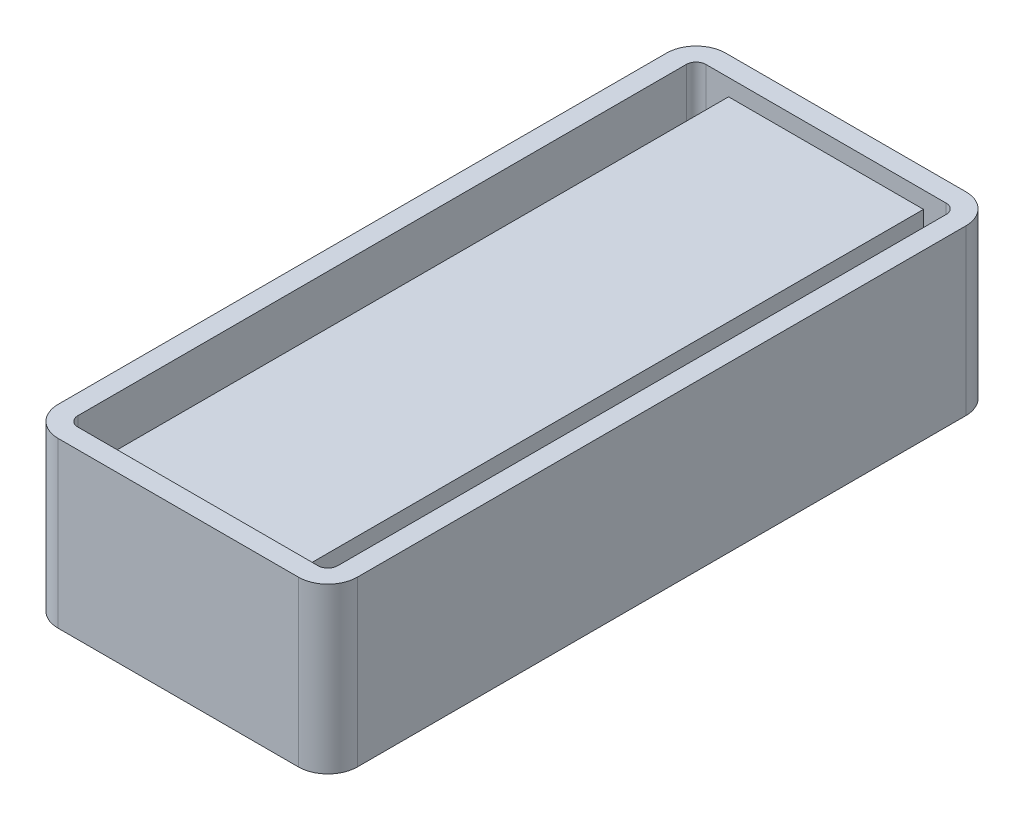
SolidWorks part; units mm, degrees
ref_plane "Front Plane" through (0, 0, 0) normal (0, 0, 1) x (1, 0, 0)
ref_plane "Top Plane" through (0, 0, 0) normal (0, 1, 0) x (1, 0, 0)
ref_plane "Right Plane" through (0, 0, 0) normal (1, 0, 0) x (0, 0, -1)
sketch "Sketch1" plane through (0, 0, 0) normal (0, 1, 0) x (1, 0, 0)
  line L0 (-15.2, 30.9) -> (-15.2, -30.9)
  line L1 (-9.9, 31.9) -> (9.9, 31.9)
  line L2 (-9.9, 31.9) -> (-9.9, -31.9)
  line L3 (-9.9, -31.9) -> (9.9, -31.9)
  line L4 (9.9, 31.9) -> (9.9, -31.9)
  line L5 (-9.9, 31.9) -> (9.9, -31.9) construction
  line L6 (-9.9, -31.9) -> (9.9, 31.9) construction
  line L7 (-12.2, 31.9) -> (12.2, 31.9)
  line L8 (-13.2, 30.9) -> (-13.2, -30.9)
  line L9 (-12.2, -31.9) -> (12.2, -31.9)
  line L10 (13.2, 30.9) -> (13.2, -30.9)
  line L11 (-13.2, 31.9) -> (13.2, -31.9) construction
  line L12 (-13.2, -31.9) -> (13.2, 31.9) construction
  line L13 (-12.2, -33.9) -> (12.2, -33.9)
  line L14 (15.2, 30.9) -> (15.2, -30.9)
  line L15 (-12.2, 33.9) -> (12.2, 33.9)
  arc A0 (-13.2, -30.9) -> (-12.2, -31.9) centre (-12.2, -30.9) ccw
  arc A1 (12.2, -31.9) -> (13.2, -30.9) centre (12.2, -30.9) ccw
  arc A2 (12.2, 31.9) -> (13.2, 30.9) centre (12.2, 30.9) cw
  arc A3 (-12.2, 31.9) -> (-13.2, 30.9) centre (-12.2, 30.9) ccw
  arc A4 (-15.2, -30.9) -> (-12.2, -33.9) centre (-12.2, -30.9) ccw
  arc A5 (12.2, -33.9) -> (15.2, -30.9) centre (12.2, -30.9) ccw
  arc A6 (12.2, 33.9) -> (15.2, 30.9) centre (12.2, 30.9) cw
  arc A7 (-12.2, 33.9) -> (-15.2, 30.9) centre (-12.2, 30.9) ccw
  point P0 (0, 0)
  point P6 (0, 0)
  point P11 (0, 0)
  dimension "D4" = 1
  dimension "D1" = 19.8
  dimension "D2" = 63.8
  dimension "D3" = 3.3
  dimension "D5" = 2
extrude "Boss-Extrude1" add sketch "Sketch1" along normal blind 15 contours L2 L9 L4 L7 | L15 A7 L0 A4 L13 A5 L14 A6 A3 L7 L2 L1 L4 A2 L10 A1 L9 L3 A0 L8
sketch "Sketch2" plane through (0, 15, 0) normal (0, 1, 0) x (1, 0, 0)
  line L0 (12.2, 31.9) -> (-12.2, 31.9)
  line L1 (-13.2, 30.9) -> (-13.2, -30.9)
  line L2 (-12.2, -31.9) -> (12.2, -31.9)
  line L3 (13.2, -30.9) -> (13.2, 30.9)
  line L4 (12.2, 33.9) -> (-12.2, 33.9)
  line L5 (-15.2, 30.9) -> (-15.2, -30.9)
  line L6 (-12.2, -33.9) -> (12.2, -33.9)
  line L7 (15.2, -30.9) -> (15.2, 30.9)
  line L8 (12.2, 33.9) -> (-12.2, 33.9)
  line L9 (-15.2, 30.9) -> (-15.2, -30.9)
  line L10 (-12.2, -33.9) -> (12.2, -33.9)
  line L11 (15.2, -30.9) -> (15.2, 30.9)
  arc A0 (-12.2, 31.9) -> (-13.2, 30.9) centre (-12.2, 30.9) ccw
  arc A1 (-13.2, -30.9) -> (-12.2, -31.9) centre (-12.2, -30.9) ccw
  arc A2 (12.2, -31.9) -> (13.2, -30.9) centre (12.2, -30.9) ccw
  arc A3 (13.2, 30.9) -> (12.2, 31.9) centre (12.2, 30.9) ccw
  arc A4 (-12.2, 33.9) -> (-15.2, 30.9) centre (-12.2, 30.9) ccw
  arc A5 (-15.2, -30.9) -> (-12.2, -33.9) centre (-12.2, -30.9) ccw
  arc A6 (12.2, -33.9) -> (15.2, -30.9) centre (12.2, -30.9) ccw
  arc A7 (15.2, 30.9) -> (12.2, 33.9) centre (12.2, 30.9) ccw
  arc A8 (-12.2, 33.9) -> (-15.2, 30.9) centre (-12.2, 30.9) ccw
  arc A9 (-15.2, -30.9) -> (-12.2, -33.9) centre (-12.2, -30.9) ccw
  arc A10 (12.2, -33.9) -> (15.2, -30.9) centre (12.2, -30.9) ccw
  arc A11 (15.2, 30.9) -> (12.2, 33.9) centre (12.2, 30.9) ccw
  dimension "D1" = 0
  dimension "D2" = 2
extrude "Boss-Extrude2" add sketch "Sketch2" along normal blind 1.7
equation "\"D1@Sketch1\"= 20.3 - 0.5"
equation "\"D2@Sketch1\"=62.3+1.5"
